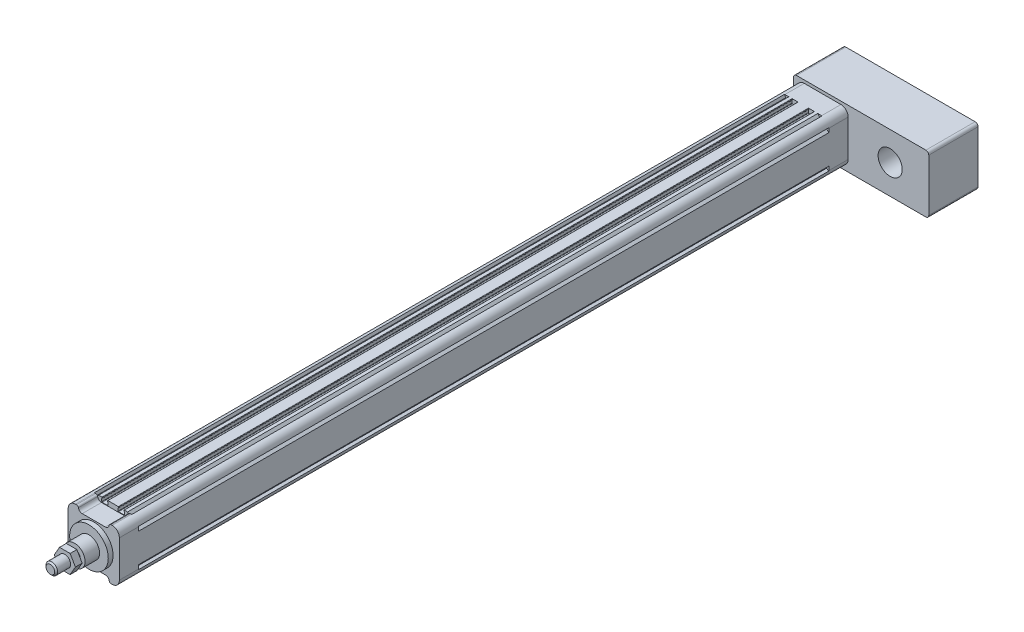
SolidWorks part; units mm, degrees
ref_plane "Front" through (0, 0, 0) normal (0, 0, 1) x (1, 0, 0)
ref_plane "Top" through (0, 0, 0) normal (0, 1, 0) x (1, 0, 0)
ref_plane "Right" through (0, 0, 0) normal (1, 0, 0) x (0, 0, -1)
sketch "草图1" plane through (0, 0, 0) normal (0, 0, 1) x (1, 0, 0)
  line L0 (19.7737, 3) -> (23.3, 3)
  line L1 (23.3, 3) -> (23.3, -3)
  line L2 (23.3, -3) -> (19.7737, -3)
  line L3 (-19.7737, -3) -> (-23.3, -3)
  line L4 (-23.3, -3) -> (-23.3, 3)
  line L5 (-23.3, 3) -> (-19.7737, 3)
  line L6 (-18.2, 24) -> (-19.4434, 26.4869)
  line L7 (-26.4869, 19.4434) -> (-24, 18.2)
  line L8 (-24, 18.2) -> (-24, 17.1)
  line L9 (-24, 17.1) -> (-26.5, 15)
  line L10 (-26.5, 15) -> (-26.5, -15)
  line L11 (-26.5, -15) -> (-24, -17.1)
  line L12 (-24, -17.1) -> (-24, -18.2)
  line L13 (-24, -18.2) -> (-26.4869, -19.4434)
  line L14 (-19.4434, -26.4869) -> (-18.2, -24)
  line L15 (-18.2, -24) -> (-17.1, -24)
  line L16 (-17.1, -24) -> (-15, -26.5)
  line L17 (-15, -26.5) -> (-11.65, -26.5)
  line L18 (-11.25, -26.1) -> (-11.25, -25.6)
  line L19 (-11.65, -25.2) -> (-11.75, -25.2)
  line L20 (-11.75, -25.2) -> (-11.75, -22.4)
  line L21 (-11.35, -22) -> (-5.65, -22)
  line L22 (-5.25, -22.4) -> (-5.25, -25.2)
  line L23 (-5.25, -25.2) -> (-5.35, -25.2)
  line L24 (-5.75, -25.6) -> (-5.75, -26.1)
  line L25 (-5.35, -26.5) -> (5.35, -26.5)
  line L26 (5.75, -26.1) -> (5.75, -25.6)
  line L27 (5.35, -25.2) -> (5.25, -25.2)
  line L28 (5.25, -25.2) -> (5.25, -22.4)
  line L29 (5.65, -22) -> (11.35, -22)
  line L30 (11.75, -22.4) -> (11.75, -25.2)
  line L31 (11.75, -25.2) -> (11.65, -25.2)
  line L32 (11.25, -25.6) -> (11.25, -26.1)
  line L33 (11.65, -26.5) -> (15, -26.5)
  line L34 (15, -26.5) -> (17.1, -24)
  line L35 (17.1, -24) -> (18.2, -24)
  line L36 (18.2, -24) -> (19.4434, -26.4869)
  line L37 (26.4869, -19.4434) -> (24, -18.2)
  line L38 (24, -18.2) -> (24, -17.1)
  line L39 (24, -17.1) -> (26.5, -15)
  line L40 (26.5, -15) -> (26.5, 15)
  line L41 (26.5, 15) -> (24, 17.1)
  line L42 (24, 17.1) -> (24, 18.2)
  line L43 (24, 18.2) -> (26.4869, 19.4434)
  line L44 (19.4434, 26.4869) -> (18.2, 24)
  line L45 (18.2, 24) -> (17.1, 24)
  line L46 (17.1, 24) -> (15, 26.5)
  line L47 (15, 26.5) -> (11.65, 26.5)
  line L48 (11.25, 26.1) -> (11.25, 25.6)
  line L49 (11.65, 25.2) -> (11.75, 25.2)
  line L50 (11.75, 25.2) -> (11.75, 22.4)
  line L51 (11.35, 22) -> (5.65, 22)
  line L52 (5.25, 22.4) -> (5.25, 25.2)
  line L53 (5.25, 25.2) -> (5.35, 25.2)
  line L54 (5.75, 25.6) -> (5.75, 26.1)
  line L55 (5.35, 26.5) -> (-5.35, 26.5)
  line L56 (-5.75, 26.1) -> (-5.75, 25.6)
  line L57 (-5.35, 25.2) -> (-5.25, 25.2)
  line L58 (-5.25, 25.2) -> (-5.25, 22.4)
  line L59 (-5.65, 22) -> (-11.35, 22)
  line L60 (-11.75, 22.4) -> (-11.75, 25.2)
  line L61 (-11.75, 25.2) -> (-11.65, 25.2)
  line L62 (-11.25, 25.6) -> (-11.25, 26.1)
  line L63 (-11.65, 26.5) -> (-15, 26.5)
  line L64 (-15, 26.5) -> (-17.1, 24)
  line L65 (-17.1, 24) -> (-18.2, 24)
  arc A0 (19.7737, 3) -> (-19.7737, 3) centre (0, 0) ccw
  arc A1 (-19.7737, -3) -> (19.7737, -3) centre (0, 0) ccw
  circle A2 centre (19, 19) radius 2.1
  circle A3 centre (19, -19) radius 2.1
  circle A4 centre (-19, -19) radius 2.1
  circle A5 centre (-19, 19) radius 2.1
  arc A6 (-19.4434, 26.4869) -> (-26.4869, 19.4434) centre (-19, 19) ccw
  arc A7 (-26.4869, -19.4434) -> (-19.4434, -26.4869) centre (-19, -19) ccw
  arc A8 (-11.65, -26.5) -> (-11.25, -26.1) centre (-11.65, -26.1) ccw
  arc A9 (-11.25, -25.6) -> (-11.65, -25.2) centre (-11.65, -25.6) ccw
  arc A10 (-11.35, -22) -> (-11.75, -22.4) centre (-11.35, -22.4) ccw
  arc A11 (-5.25, -22.4) -> (-5.65, -22) centre (-5.65, -22.4) ccw
  arc A12 (-5.35, -25.2) -> (-5.75, -25.6) centre (-5.35, -25.6) ccw
  arc A13 (-5.75, -26.1) -> (-5.35, -26.5) centre (-5.35, -26.1) ccw
  arc A14 (5.35, -26.5) -> (5.75, -26.1) centre (5.35, -26.1) ccw
  arc A15 (5.75, -25.6) -> (5.35, -25.2) centre (5.35, -25.6) ccw
  arc A16 (5.65, -22) -> (5.25, -22.4) centre (5.65, -22.4) ccw
  arc A17 (11.75, -22.4) -> (11.35, -22) centre (11.35, -22.4) ccw
  arc A18 (11.65, -25.2) -> (11.25, -25.6) centre (11.65, -25.6) ccw
  arc A19 (11.25, -26.1) -> (11.65, -26.5) centre (11.65, -26.1) ccw
  arc A20 (19.4434, -26.4869) -> (26.4869, -19.4434) centre (19, -19) ccw
  arc A21 (26.4869, 19.4434) -> (19.4434, 26.4869) centre (19, 19) ccw
  arc A22 (11.65, 26.5) -> (11.25, 26.1) centre (11.65, 26.1) ccw
  arc A23 (11.25, 25.6) -> (11.65, 25.2) centre (11.65, 25.6) ccw
  arc A24 (11.35, 22) -> (11.75, 22.4) centre (11.35, 22.4) ccw
  arc A25 (5.25, 22.4) -> (5.65, 22) centre (5.65, 22.4) ccw
  arc A26 (5.35, 25.2) -> (5.75, 25.6) centre (5.35, 25.6) ccw
  arc A27 (5.75, 26.1) -> (5.35, 26.5) centre (5.35, 26.1) ccw
  arc A28 (-5.35, 26.5) -> (-5.75, 26.1) centre (-5.35, 26.1) ccw
  arc A29 (-5.75, 25.6) -> (-5.35, 25.2) centre (-5.35, 25.6) ccw
  arc A30 (-5.65, 22) -> (-5.25, 22.4) centre (-5.65, 22.4) ccw
  arc A31 (-11.75, 22.4) -> (-11.35, 22) centre (-11.35, 22.4) ccw
  arc A32 (-11.65, 25.2) -> (-11.25, 25.6) centre (-11.65, 25.6) ccw
  arc A33 (-11.25, 26.1) -> (-11.65, 26.5) centre (-11.65, 26.1) ccw
extrude "凸台-拉伸1" add sketch "草图1" along normal blind 715
sketch "草图6" plane through (0, 0, 715) normal (0, 0, 1) x (1, 0, 0)
  line L0 (0, 0) -> (19, 0) construction
  line L2 (-26.5, -19) -> (-26.5, 19)
  line L3 (-19, 26.5) -> (-17.9161, 26.5)
  line L4 (26.5, -19) -> (26.5, 19)
  line L5 (-26.5, -26.5) -> (26.5, 26.5) construction
  line L6 (-26.5, 26.5) -> (26.5, -26.5) construction
  line L7 (-12, 21.5) -> (12, 21.5)
  line L9 (19, 26.5) -> (17.9161, 26.5)
  line L10 (19, -26.5) -> (17.9161, -26.5)
  line L11 (-12, -21.5) -> (12, -21.5)
  line L12 (-19, -26.5) -> (-17.9161, -26.5)
  arc A0 (12, 21.5) -> (15.9441, 24.8333) centre (12, 25.5) ccw
  arc A1 (-15.9441, 24.8333) -> (-12, 21.5) centre (-12, 25.5) ccw
  arc A2 (-15.9441, 24.8333) -> (-17.9161, 26.5) centre (-17.9161, 24.5) ccw
  arc A3 (15.9441, 24.8333) -> (17.9161, 26.5) centre (17.9161, 24.5) cw
  arc A4 (-26.5, -19) -> (-19, -26.5) centre (-19, -19) ccw
  arc A5 (19, -26.5) -> (26.5, -19) centre (19, -19) ccw
  arc A6 (26.5, 19) -> (19, 26.5) centre (19, 19) ccw
  arc A7 (-26.5, 19) -> (-19, 26.5) centre (-19, 19) cw
  arc A8 (15.9441, -24.8333) -> (17.9161, -26.5) centre (17.9161, -24.5) ccw
  arc A9 (12, -21.5) -> (15.9441, -24.8333) centre (12, -25.5) cw
  arc A10 (-15.9441, -24.8333) -> (-12, -21.5) centre (-12, -25.5) cw
  arc A11 (-15.9441, -24.8333) -> (-17.9161, -26.5) centre (-17.9161, -24.5) cw
  point P0 (0, 0)
  point P9 (0, 21.5)
  point P13 (20, 20.8461)
  point P16 (-12, 20.8461)
  dimension "D5" = 4
  dimension "D6" = 2
  dimension "D7" = 2
  dimension "D9" = 7.5
  dimension "D1" = 53
  dimension "D2" = 53
  dimension "D3" = 26.5
  dimension "D4" = 24
  dimension "D8" = 5
extrude "凸台-拉伸2" add sketch "草图6" along normal blind 20
sketch "草图7" plane through (0, 0, 735) normal (0, 0, 1) x (1, 0, 0)
  circle A0 centre (0, 0) radius 20
  dimension "D1" = 40
extrude "凸台-拉伸3" add sketch "草图7" along normal blind 5
sketch "草图9" plane through (0, 0, 740) normal (0, 0, 1) x (1, 0, 0)
  circle A0 centre (0, 0) radius 11
  dimension "D1" = 22
extrude "凸台-拉伸4" add sketch "草图9" along normal blind 15
sketch "草图10" plane through (0, 0, 755) normal (0, 0, 1) x (1, 0, 0)
  circle A0 centre (0, 0) radius 6
  dimension "D1" = 12
extrude "凸台-拉伸5" add sketch "草图10" along normal blind 25
sketch "草图11" plane through (0, 0, 0) normal (0, 0, -1) x (-1, 0, 0)
  line L1 (-19, -26.5) -> (19, -26.5)
  line L2 (-26.5, -19) -> (-26.5, 19)
  line L3 (-19, 26.5) -> (19, 26.5)
  line L4 (26.5, -19) -> (26.5, 19)
  line L5 (-26.5, -26.5) -> (26.5, 26.5) construction
  line L6 (-26.5, 26.5) -> (26.5, -26.5) construction
  arc A0 (-26.5, -19) -> (-19, -26.5) centre (-19, -19) ccw
  arc A1 (19, -26.5) -> (26.5, -19) centre (19, -19) ccw
  arc A2 (26.5, 19) -> (19, 26.5) centre (19, 19) ccw
  arc A3 (-26.5, 19) -> (-19, 26.5) centre (-19, 19) cw
  point P0 (0, 0)
  dimension "D3" = 7.5
  dimension "D1" = 53
  dimension "D2" = 53
extrude "凸台-拉伸6" add sketch "草图11" along normal blind 20
sketch "草图12" plane through (0, 0, -20) normal (0, 0, -1) x (-1, 0, 0)
  line L1 (-107, -30.4042) -> (27, -30.4042)
  line L2 (-110, -27.4042) -> (-110, 26.5958)
  line L3 (-107, 29.5958) -> (27, 29.5958)
  line L4 (30, -27.4042) -> (30, 26.5958)
  line L5 (-110, -30.4042) -> (30, 29.5958) construction
  line L6 (-110, 29.5958) -> (30, -30.4042) construction
  arc A0 (27, 29.5958) -> (30, 26.5958) centre (27, 26.5958) cw
  arc A1 (30, -27.4042) -> (27, -30.4042) centre (27, -27.4042) cw
  arc A2 (-110, -27.4042) -> (-107, -30.4042) centre (-107, -27.4042) ccw
  arc A3 (-110, 26.5958) -> (-107, 29.5958) centre (-107, 26.5958) cw
  point P0 (-40, -0.4042)
  dimension "D4" = 3
  dimension "D1" = 60
  dimension "D2" = 140
  dimension "D3" = 30
extrude "凸台-拉伸7" add sketch "草图12" along normal blind 51
sketch "草图13" plane through (0, 0, -20) normal (0, 0, 1) x (1, 0, 0)
  circle A0 centre (70, 0) radius 12.5
  dimension "D2" = 25
  dimension "D1" = 70
extrude "切除-拉伸2" cut sketch "草图13" against normal blind 30
hole_wizard "M6 螺纹孔1" positions "草图14" profile "草图15" tap size "M6" standard "GB"
sketch "草图14" plane through (0, 0, -71) normal (0, 0, -1) x (-1, 0, 0)
  line L0 (30, -27.4042) -> (30, 26.5958) construction
  point P0 (19, -19)
  dimension "D1" = 11
  dimension "D2" = 19
sketch "草图15" plane through (-19, -19, -71) normal (1, 0, 0) x (0, 1, 0)
  line L0 (0, 0) -> (0, 16.5022)
  line L1 (0, 16.5022) -> (2.5, 15)
  line L2 (2.5, 15) -> (2.5, 0)
  line L5 (2.5, 0) -> (0, 0)
  line L10 (0, 16.5022) -> (-2.5, 15) construction
  line L11 (0, -6.35) -> (0, 107.95) construction
  dimension "螺纹孔钻头直径" = 5
  dimension "螺纹孔钻头深度" = 15
  dimension "导头角度" = 118
cosmetic thread "孔螺蚊线4" parameters "D1"=12, "D2"=6
pattern_linear "阵列(线性)1" count 2 spacing 38 along (0, 1, 0) count 2 spacing 38 along (1, 0, 0) of "M6 螺纹孔1"
hole_wizard "M6 螺纹孔2" positions "草图16" profile "草图17" tap size "M6" standard "GB"
sketch "草图16" plane through (0, 0, -71) normal (0, 0, -1) x (-1, 0, 0)
  circle A1 centre (-19, 19) radius 2.5 construction
  circle A2 centre (-19, -19) radius 2.5 construction
  point P0 (-84, -19)
  point P2 (-84, 19)
  dimension "D3" = 65
  dimension "D1" = 19
  dimension "D2" = 19
  dimension "D4" = 65
sketch "草图17" plane through (84, -19, -71) normal (1, 0, 0) x (0, 1, 0)
  line L0 (0, 0) -> (0, 16.5022)
  line L1 (0, 16.5022) -> (2.5, 15)
  line L2 (2.5, 15) -> (2.5, 0)
  line L5 (2.5, 0) -> (0, 0)
  line L10 (0, 16.5022) -> (-2.5, 15) construction
  line L11 (0, -6.35) -> (0, 107.95) construction
  dimension "螺纹孔钻头直径" = 5
  dimension "螺纹孔钻头深度" = 15
  dimension "导头角度" = 118
cosmetic thread "孔螺蚊线5" parameters "D1"=12, "D2"=6
cosmetic thread "孔螺蚊线6" parameters "D1"=12, "D2"=6
hole_wizard "M6 螺纹孔3" positions "草图19" profile "草图20" tap size "M6" standard "GB"
sketch "草图19" plane through (-26.5, 0, 0) normal (-1, 0, 0) x (0, 0, 1)
  line L0 (735, 19) -> (735, -19) construction
  point P0 (725, 11)
  point P2 (725, -11)
  dimension "D1" = 10
  dimension "D2" = 10
  dimension "D3" = 22
  dimension "D4" = 11
sketch "草图20" plane through (-26.5, 11, 725) normal (0, 1, 0) x (0, 0, 1)
  line L0 (0, 0) -> (0, 16.5022)
  line L1 (0, 16.5022) -> (2.5, 15)
  line L2 (2.5, 15) -> (2.5, 0)
  line L5 (2.5, 0) -> (0, 0)
  line L10 (0, 16.5022) -> (-2.5, 15) construction
  line L11 (0, -6.35) -> (0, 107.95) construction
  dimension "螺纹孔钻头直径" = 5
  dimension "螺纹孔钻头深度" = 15
  dimension "导头角度" = 118
cosmetic thread "孔螺蚊线7" parameters "D1"=12, "D2"=6
cosmetic thread "孔螺蚊线8" parameters "D1"=12, "D2"=6
hole_wizard "M6 螺纹孔4" positions "草图21" profile "草图22" tap size "M6" standard "GB"
sketch "草图21" plane through (-26.5, 0, 0) normal (-1, 0, 0) x (0, 0, 1)
  line L0 (-20, -27.4042) -> (-20, 26.5958) construction
  line L1 (-20, -19) -> (-20, 19) construction
  point P0 (-10, 11)
  point P2 (-10, -11)
  dimension "D1" = 10
  dimension "D2" = 10
  dimension "D3" = 11
  dimension "D4" = 11
sketch "草图22" plane through (-26.5, 11, -10) normal (0, 1, 0) x (0, 0, 1)
  line L0 (0, 0) -> (0, 16.5022)
  line L1 (0, 16.5022) -> (2.5, 15)
  line L2 (2.5, 15) -> (2.5, 0)
  line L5 (2.5, 0) -> (0, 0)
  line L10 (0, 16.5022) -> (-2.5, 15) construction
  line L11 (0, -6.35) -> (0, 107.95) construction
  dimension "螺纹孔钻头直径" = 5
  dimension "螺纹孔钻头深度" = 15
  dimension "导头角度" = 118
cosmetic thread "孔螺蚊线9" parameters "D1"=12, "D2"=6
cosmetic thread "孔螺蚊线10" parameters "D1"=12, "D2"=6
chamfer "倒角1" distance 1.5 angle 45 1 edges at (6, 0, 780)
sketch "草图23" plane through (0, 0, 755) normal (0, 0, 1) x (1, 0, 0)
  line L1 (10.9697, 0) -> (5.4848, 9.5)
  line L2 (5.4848, 9.5) -> (-5.4848, 9.5)
  line L3 (-5.4848, 9.5) -> (-10.9697, 0)
  line L4 (-10.9697, 0) -> (-5.4848, -9.5)
  line L5 (-5.4848, -9.5) -> (5.4848, -9.5)
  line L6 (5.4848, -9.5) -> (10.9697, 0)
  circle A0 centre (0, 0) radius 9.5 construction
  dimension "D1" = 19
extrude "凸台-拉伸8" add sketch "草图23" along normal blind 7 from offset 3
